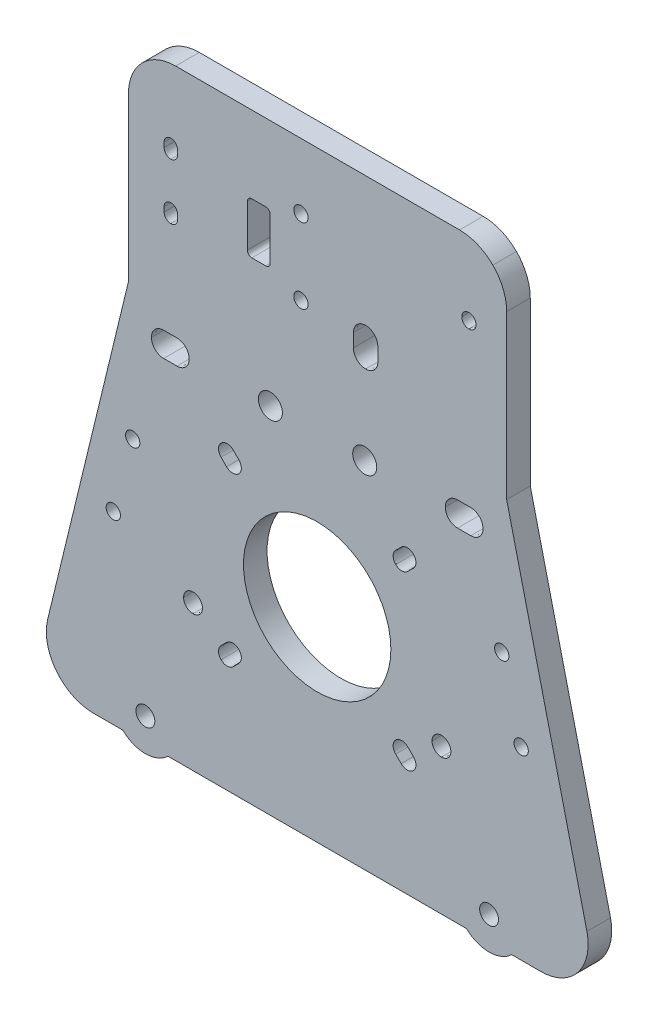
SolidWorks part; units mm, degrees
ref_plane "Front Plane" through (0, 0, 0) normal (0, 0, 1) x (1, 0, 0)
ref_plane "Top Plane" through (0, 0, 0) normal (0, 1, 0) x (1, 0, 0)
ref_plane "Right Plane" through (0, 0, 0) normal (1, 0, 0) x (0, 0, -1)
sketch "Model" plane through (0, 0, 0) normal (0, 0, 1) x (1, 0, 0)
  line L270 (-190.2054, -38.689) -> (-186.4527, -38.689)
  line L271 (-185.2542, -39.8875) -> (-185.2542, -51.2593)
  line L272 (-186.4527, -52.4579) -> (-190.2054, -52.4579)
  line L273 (-191.4039, -51.2593) -> (-191.4039, -39.8875)
  line L274 (-210.2034, -37.272) -> (-210.2034, -38.5411)
  line L275 (-213.814, -38.5411) -> (-213.814, -37.272)
  line L276 (-210.2034, -52.3121) -> (-210.2034, -53.5812)
  line L277 (-213.814, -53.5812) -> (-213.814, -52.3121)
  line L278 (-146.7064, -103.0735) -> (-148.1907, -104.5577)
  line L279 (-151.4757, -101.2723) -> (-149.9914, -99.7884)
  line L280 (-193.7055, -148.7926) -> (-195.1911, -150.2781)
  line L281 (-198.4765, -146.9927) -> (-196.991, -145.5072)
  line L282 (-196.991, -104.5577) -> (-198.4765, -103.0735)
  line L283 (-195.1911, -99.788) -> (-193.7055, -101.2723)
  line L284 (-149.9914, -150.2778) -> (-151.4757, -148.7923)
  line L285 (-148.1907, -145.5072) -> (-146.7064, -146.9927)
  line L286 (-213.9323, -81.1983) -> (-210.3512, -81.1983)
  line L287 (-210.3512, -87.7771) -> (-213.9323, -87.7771)
  line L288 (-134.83, -81.1983) -> (-131.2501, -81.1983)
  line L289 (-131.2501, -87.7771) -> (-134.83, -87.7771)
  line L290 (-156.2737, -56.1744) -> (-156.2737, -59.7564)
  line L291 (-162.8529, -59.7564) -> (-162.8529, -56.1744)
  line L292 (-223.3908, -30.6861) -> (-223.3908, -74.5286)
  line L293 (-223.3908, -74.5286) -> (-245.197, -164.3888)
  line L294 (-232.8227, -179.947) -> (-224.9303, -179.947)
  line L295 (-212.7815, -179.947) -> (-132.4009, -179.947)
  line L296 (-120.2522, -179.947) -> (-112.3602, -179.947)
  line L297 (-99.9855, -164.3888) -> (-121.5896, -74.5286)
  line L298 (-121.5896, -74.5286) -> (-121.5896, -30.6861)
  line L299 (-134.2894, -17.9863) -> (-210.6909, -17.9863)
  circle A0 centre (-185.2043, -84.4885) radius 3.2404
  circle A1 centre (-159.8043, -84.4885) radius 3.2404
  circle A2 centre (-172.6049, -125.0331) radius 19.8387
  circle A3 centre (-218.8561, -173.597) radius 2.5396
  circle A4 centre (-126.3263, -173.597) radius 2.5396
  circle A5 centre (-176.9718, -35.5703) radius 1.9251
  circle A6 centre (-176.9718, -55.7487) radius 1.9249
  circle A7 centre (-222.2685, -110.7401) radius 1.9251
  circle A8 centre (-227.4916, -130.231) radius 1.9255
  circle A9 centre (-122.9141, -110.7401) radius 1.9251
  circle A10 centre (-117.6912, -130.231) radius 1.9251
  spline S528 degree 3 poles (-186.4527, -38.689) (-185.7891, -38.689) (-185.2542, -39.2235) (-185.2542, -39.8875) knots 0.111111 0.111111 0.111111 0.111111 0.222222 0.222222 0.222222 0.222222
  spline S529 degree 3 poles (-185.2542, -51.2593) (-185.2542, -51.9238) (-185.7891, -52.4579) (-186.4527, -52.4579) knots 0.333333 0.333333 0.333333 0.333333 0.444444 0.444444 0.444444 0.444444
  spline S530 degree 3 poles (-190.2054, -52.4579) (-190.8694, -52.4579) (-191.4039, -51.9238) (-191.4039, -51.2593) knots 0.555556 0.555556 0.555556 0.555556 0.666667 0.666667 0.666667 0.666667
  spline S531 degree 3 poles (-191.4039, -39.8875) (-191.4039, -39.2235) (-190.8694, -38.689) (-190.2054, -38.689) knots 0.777778 0.777778 0.777778 0.777778 1 1 1 1
  spline S540 degree 3 poles (-212.0087, -35.4667) (-211.0082, -35.4667) (-210.2034, -36.2715) (-210.2034, -37.272) knots 0 0 0 0 0.142857 0.142857 0.142857 0.142857
  spline S541 degree 3 poles (-210.2034, -38.5411) (-210.2034, -39.5416) (-211.0082, -40.3465) (-212.0087, -40.3465) knots 0.285714 0.285714 0.285714 0.285714 0.428571 0.428571 0.428571 0.428571
  spline S542 degree 3 poles (-212.0087, -40.3465) (-213.0091, -40.3465) (-213.814, -39.5416) (-213.814, -38.5411) knots 0.428571 0.428571 0.428571 0.428571 0.571429 0.571429 0.571429 0.571429
  spline S543 degree 3 poles (-213.814, -37.272) (-213.814, -36.2715) (-213.0091, -35.4667) (-212.0087, -35.4667) knots 0.714286 0.714286 0.714286 0.714286 1 1 1 1
  spline S544 degree 3 poles (-212.0087, -50.5068) (-211.0082, -50.5068) (-210.2034, -51.3116) (-210.2034, -52.3121) knots 0 0 0 0 0.142857 0.142857 0.142857 0.142857
  spline S545 degree 3 poles (-210.2034, -53.5812) (-210.2034, -54.5817) (-211.0082, -55.3861) (-212.0087, -55.3861) knots 0.285714 0.285714 0.285714 0.285714 0.428571 0.428571 0.428571 0.428571
  spline S546 degree 3 poles (-212.0087, -55.3861) (-213.0091, -55.3861) (-213.814, -54.5817) (-213.814, -53.5812) knots 0.428571 0.428571 0.428571 0.428571 0.571429 0.571429 0.571429 0.571429
  spline S547 degree 3 poles (-213.814, -52.3121) (-213.814, -51.3116) (-213.0091, -50.5068) (-212.0087, -50.5068) knots 0.714286 0.714286 0.714286 0.714286 1 1 1 1
  spline S548 degree 3 poles (-129.8269, -37.9074) (-129.8269, -38.9701) (-130.6878, -39.8311) (-131.7506, -39.8311) knots 0 0 0 0 0.2 0.2 0.2 0.2
  spline S549 degree 3 poles (-131.7506, -39.8311) (-132.8142, -39.8311) (-133.6755, -38.9701) (-133.6755, -37.9074) knots 0.2 0.2 0.2 0.2 0.4 0.4 0.4 0.4
  spline S550 degree 3 poles (-133.6755, -37.9074) (-133.6755, -36.8438) (-132.8142, -35.9821) (-131.7506, -35.9821) knots 0.4 0.4 0.4 0.4 0.6 0.6 0.6 0.6
  spline S551 degree 3 poles (-131.7506, -35.9821) (-130.6878, -35.9821) (-129.8269, -36.8438) (-129.8269, -37.9074) knots 0.6 0.6 0.6 0.6 1 1 1 1
  spline S552 degree 3 poles (-136.6079, -140.801) (-136.6079, -139.3985) (-137.745, -138.2615) (-139.1479, -138.2615) knots 0 0 0 0 0.2 0.2 0.2 0.2
  spline S553 degree 3 poles (-139.1479, -138.2615) (-140.5504, -138.2615) (-141.6875, -139.3985) (-141.6875, -140.801) knots 0.2 0.2 0.2 0.2 0.4 0.4 0.4 0.4
  spline S554 degree 3 poles (-141.6875, -140.801) (-141.6875, -142.2041) (-140.5504, -143.3408) (-139.1479, -143.3408) knots 0.4 0.4 0.4 0.4 0.6 0.6 0.6 0.6
  spline S555 degree 3 poles (-139.1479, -143.3408) (-137.745, -143.3408) (-136.6079, -142.2041) (-136.6079, -140.801) knots 0.6 0.6 0.6 0.6 1 1 1 1
  spline S556 degree 3 poles (-203.4938, -140.801) (-203.4938, -139.3985) (-204.6321, -138.2615) (-206.035, -138.2615) knots 0 0 0 0 0.2 0.2 0.2 0.2
  spline S557 degree 3 poles (-206.035, -138.2615) (-207.4379, -138.2615) (-208.5745, -139.3985) (-208.5745, -140.801) knots 0.2 0.2 0.2 0.2 0.4 0.4 0.4 0.4
  spline S558 degree 3 poles (-208.5745, -140.801) (-208.5745, -142.2041) (-207.4379, -143.3408) (-206.035, -143.3408) knots 0.4 0.4 0.4 0.4 0.6 0.6 0.6 0.6
  spline S559 degree 3 poles (-206.035, -143.3408) (-204.6321, -143.3408) (-203.4938, -142.2041) (-203.4938, -140.801) knots 0.6 0.6 0.6 0.6 1 1 1 1
  spline S564 degree 3 poles (-146.7064, -99.788) (-145.7952, -100.6975) (-145.7956, -102.1623) (-146.7064, -103.0735) knots 0 0 0 0 0.142857 0.142857 0.142857 0.142857
  spline S565 degree 3 poles (-148.1907, -104.5577) (-149.1014, -105.4685) (-150.5662, -105.4685) (-151.4757, -104.5577) knots 0.285714 0.285714 0.285714 0.285714 0.428571 0.428571 0.428571 0.428571
  spline S566 degree 3 poles (-151.4757, -104.5577) (-152.3864, -103.6482) (-152.3864, -102.1835) (-151.4757, -101.2723) knots 0.428571 0.428571 0.428571 0.428571 0.571429 0.571429 0.571429 0.571429
  spline S567 degree 3 poles (-149.9914, -99.7884) (-149.0807, -98.8773) (-147.6155, -98.8773) (-146.7064, -99.788) knots 0.714286 0.714286 0.714286 0.714286 1 1 1 1
  spline S568 degree 3 poles (-193.7051, -145.5072) (-192.7956, -146.4181) (-192.796, -147.8832) (-193.7055, -148.7926) knots 0 0 0 0 0.142857 0.142857 0.142857 0.142857
  spline S569 degree 3 poles (-195.1911, -150.2781) (-196.1006, -151.1876) (-197.5653, -151.1876) (-198.4761, -150.2781) knots 0.285714 0.285714 0.285714 0.285714 0.428571 0.428571 0.428571 0.428571
  spline S570 degree 3 poles (-198.4761, -150.2781) (-199.386, -149.3669) (-199.386, -147.9022) (-198.4765, -146.9927) knots 0.428571 0.428571 0.428571 0.428571 0.571429 0.571429 0.571429 0.571429
  spline S571 degree 3 poles (-196.991, -145.5072) (-196.0815, -144.5978) (-194.6163, -144.5973) (-193.7051, -145.5072) knots 0.714286 0.714286 0.714286 0.714286 1 1 1 1
  spline S572 degree 3 poles (-193.7055, -104.5569) (-194.6163, -105.4681) (-196.0815, -105.4685) (-196.991, -104.5577) knots 0 0 0 0 0.142857 0.142857 0.142857 0.142857
  spline S573 degree 3 poles (-198.4765, -103.0735) (-199.386, -102.1623) (-199.3856, -100.6975) (-198.4761, -99.788) knots 0.285714 0.285714 0.285714 0.285714 0.428571 0.428571 0.428571 0.428571
  spline S574 degree 3 poles (-198.4761, -99.788) (-197.5653, -98.8773) (-196.1006, -98.8773) (-195.1911, -99.788) knots 0.428571 0.428571 0.428571 0.428571 0.571429 0.571429 0.571429 0.571429
  spline S575 degree 3 poles (-193.7055, -101.2723) (-192.796, -102.183) (-192.796, -103.6478) (-193.7055, -104.5569) knots 0.714286 0.714286 0.714286 0.714286 1 1 1 1
  spline S576 degree 3 poles (-146.7064, -150.2781) (-147.6155, -151.1876) (-149.0807, -151.1873) (-149.9914, -150.2778) knots 0 0 0 0 0.142857 0.142857 0.142857 0.142857
  spline S577 degree 3 poles (-151.4757, -148.7923) (-152.3864, -147.8828) (-152.3864, -146.4181) (-151.4757, -145.5072) knots 0.285714 0.285714 0.285714 0.285714 0.428571 0.428571 0.428571 0.428571
  spline S578 degree 3 poles (-151.4757, -145.5072) (-150.5662, -144.5978) (-149.1014, -144.5978) (-148.1907, -145.5072) knots 0.428571 0.428571 0.428571 0.428571 0.571429 0.571429 0.571429 0.571429
  spline S579 degree 3 poles (-146.7064, -146.9927) (-145.7956, -147.9022) (-145.7952, -149.3672) (-146.7064, -150.2781) knots 0.714286 0.714286 0.714286 0.714286 1 1 1 1
  spline S596 degree 3 poles (-210.3512, -81.1983) (-208.5289, -81.1983) (-207.0612, -82.666) (-207.0612, -84.4875) knots 0.142857 0.142857 0.142857 0.142857 0.285714 0.285714 0.285714 0.285714
  spline S597 degree 3 poles (-207.0612, -84.4875) (-207.0612, -86.3107) (-208.5289, -87.7771) (-210.3512, -87.7771) knots 0.285714 0.285714 0.285714 0.285714 0.428571 0.428571 0.428571 0.428571
  spline S598 degree 3 poles (-213.9323, -87.7771) (-215.7543, -87.7771) (-217.2215, -86.3107) (-217.2215, -84.4875) knots 0.571429 0.571429 0.571429 0.571429 0.714286 0.714286 0.714286 0.714286
  spline S599 degree 3 poles (-217.2215, -84.4875) (-217.2215, -82.666) (-215.7543, -81.1983) (-213.9323, -81.1983) knots 0.714286 0.714286 0.714286 0.714286 1 1 1 1
  spline S600 degree 3 poles (-131.2501, -81.1983) (-129.427, -81.1983) (-127.961, -82.666) (-127.961, -84.4875) knots 0.142857 0.142857 0.142857 0.142857 0.285714 0.285714 0.285714 0.285714
  spline S601 degree 3 poles (-127.961, -84.4875) (-127.961, -86.3107) (-129.427, -87.7771) (-131.2501, -87.7771) knots 0.285714 0.285714 0.285714 0.285714 0.428571 0.428571 0.428571 0.428571
  spline S602 degree 3 poles (-134.83, -87.7771) (-136.6532, -87.7771) (-138.12, -86.3107) (-138.12, -84.4875) knots 0.571429 0.571429 0.571429 0.571429 0.714286 0.714286 0.714286 0.714286
  spline S603 degree 3 poles (-138.12, -84.4875) (-138.12, -82.666) (-136.6532, -81.1983) (-134.83, -81.1983) knots 0.714286 0.714286 0.714286 0.714286 1 1 1 1
  spline S604 degree 3 poles (-156.2737, -59.7564) (-156.2737, -61.5779) (-157.7401, -63.0455) (-159.5637, -63.0455) knots 0.142857 0.142857 0.142857 0.142857 0.285714 0.285714 0.285714 0.285714
  spline S605 degree 3 poles (-159.5637, -63.0455) (-161.3852, -63.0455) (-162.8529, -61.5779) (-162.8529, -59.7564) knots 0.285714 0.285714 0.285714 0.285714 0.428571 0.428571 0.428571 0.428571
  spline S606 degree 3 poles (-162.8529, -56.1744) (-162.8529, -54.3529) (-161.3852, -52.8852) (-159.5637, -52.8852) knots 0.571429 0.571429 0.571429 0.571429 0.714286 0.714286 0.714286 0.714286
  spline S607 degree 3 poles (-159.5637, -52.8852) (-157.7401, -52.8852) (-156.2737, -54.3529) (-156.2737, -56.1744) knots 0.714286 0.714286 0.714286 0.714286 1 1 1 1
  spline S608 degree 3 poles (-210.6909, -17.9863) (-214.059, -17.9863) (-217.2888, -19.3243) (-219.6718, -21.7057) knots 0 0 0 0 0.047619 0.047619 0.047619 0.047619
  spline S609 degree 3 poles (-219.6718, -21.7057) (-222.0531, -24.0883) (-223.3908, -27.3189) (-223.3908, -30.6861) knots 0.047619 0.047619 0.047619 0.047619 0.095238 0.095238 0.095238 0.095238
  spline S610 degree 3 poles (-245.197, -164.3888) (-246.0683, -168.1592) (-245.1712, -172.1224) (-242.7625, -175.1514) knots 0.190476 0.190476 0.190476 0.190476 0.238095 0.238095 0.238095 0.238095
  spline S611 degree 3 poles (-242.7625, -175.1514) (-240.3517, -178.1818) (-236.6933, -179.947) (-232.8227, -179.947) knots 0.238095 0.238095 0.238095 0.238095 0.285714 0.285714 0.285714 0.285714
  spline S612 degree 3 poles (-224.9303, -179.947) (-223.3514, -181.4573) (-221.2126, -182.3861) (-218.8561, -182.3861) knots 0.333333 0.333333 0.333333 0.333333 0.380952 0.380952 0.380952 0.380952
  spline S613 degree 3 poles (-218.8561, -182.3861) (-216.4981, -182.3861) (-214.3597, -181.4573) (-212.7815, -179.947) knots 0.380952 0.380952 0.380952 0.380952 0.428571 0.428571 0.428571 0.428571
  spline S614 degree 3 poles (-132.4009, -179.947) (-130.8216, -181.4573) (-128.6832, -182.3861) (-126.3263, -182.3861) knots 0.47619 0.47619 0.47619 0.47619 0.52381 0.52381 0.52381 0.52381
  spline S615 degree 3 poles (-126.3263, -182.3861) (-123.9687, -182.3861) (-121.8299, -181.4573) (-120.2522, -179.947) knots 0.52381 0.52381 0.52381 0.52381 0.571429 0.571429 0.571429 0.571429
  spline S616 degree 3 poles (-112.3602, -179.947) (-108.4892, -179.947) (-104.8291, -178.1818) (-102.4204, -175.1514) knots 0.619048 0.619048 0.619048 0.619048 0.666667 0.666667 0.666667 0.666667
  spline S617 degree 3 poles (-102.4204, -175.1514) (-100.01, -172.1224) (-99.1142, -168.1592) (-99.9855, -164.3888) knots 0.666667 0.666667 0.666667 0.666667 0.714286 0.714286 0.714286 0.714286
  spline S618 degree 3 poles (-121.5896, -30.6861) (-121.5896, -27.3189) (-122.9277, -24.0883) (-125.309, -21.7057) knots 0.809524 0.809524 0.809524 0.809524 0.857143 0.857143 0.857143 0.857143
  spline S619 degree 3 poles (-125.309, -21.7057) (-127.6916, -19.3243) (-130.9214, -17.9863) (-134.2894, -17.9863) knots 0.857143 0.857143 0.857143 0.857143 0.904762 0.904762 0.904762 0.904762
  dimension "D2" = 38.2147
  dimension "D3" = 25.4
  dimension "D1" = 38.1865
extrude "Boss-Extrude1" add sketch "Model" along normal blind 6.35
